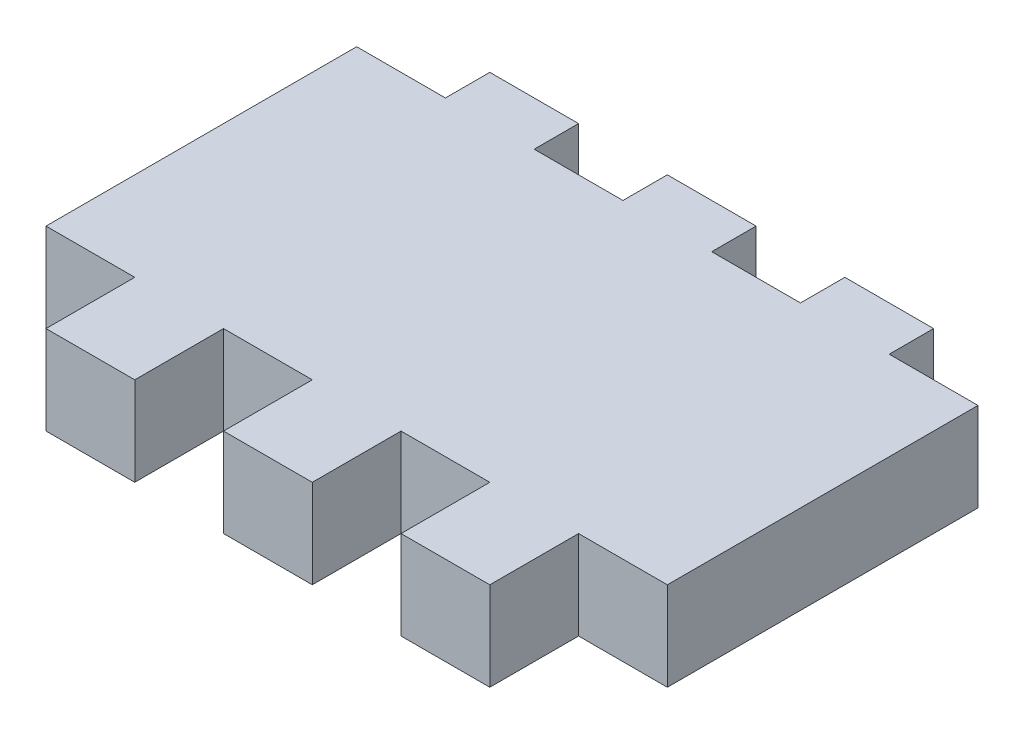
SolidWorks part; units mm, degrees
material "Acrylic (Medium-high impact)"
ref_plane "Front Plane" through (0, 0, 0) normal (0, 0, 1) x (1, 0, 0)
ref_plane "Top Plane" through (0, 0, 0) normal (0, 1, 0) x (1, 0, 0)
ref_plane "Right Plane" through (0, 0, 0) normal (1, 0, 0) x (0, 0, -1)
sketch "Sketch1" plane through (0, 0, 0) normal (0, 1, 0) x (1, 0, 0)
  line L1 (-35, -25) -> (35, -25)
  line L2 (-35, -25) -> (-35, 25)
  line L3 (-35, 25) -> (35, 25)
  line L4 (35, -25) -> (35, 25)
  line L5 (-35, -25) -> (35, 25) construction
  line L6 (-35, 25) -> (35, -25) construction
  point P0 (0, 0)
  dimension "D1" = 70
  dimension "D2" = 50
extrude "Boss-Extrude1" add sketch "Sketch1" along normal blind 10
sketch "Sketch2" plane through (0, 10, 0) normal (0, 1, 0) x (1, 0, 0)
  line L1 (-35, 25) -> (-25, 25)
  line L2 (-35, 25) -> (-35, 20)
  line L3 (-35, 20) -> (-25, 20)
  line L4 (-25, 25) -> (-25, 20)
  line L5 (-35, -25) -> (-25, -25)
  line L6 (-35, -25) -> (-35, -15)
  line L7 (-35, -15) -> (-25, -15)
  line L8 (-25, -25) -> (-25, -15)
  dimension "D1" = 10
  dimension "D2" = 5
  dimension "D3" = 10
  dimension "D4" = 10
extrude "Cut-Extrude1" cut sketch "Sketch2" against normal through all
pattern_linear "LPattern1" count 4 spacing 20 along (1, 0, 0) of "Cut-Extrude1"
